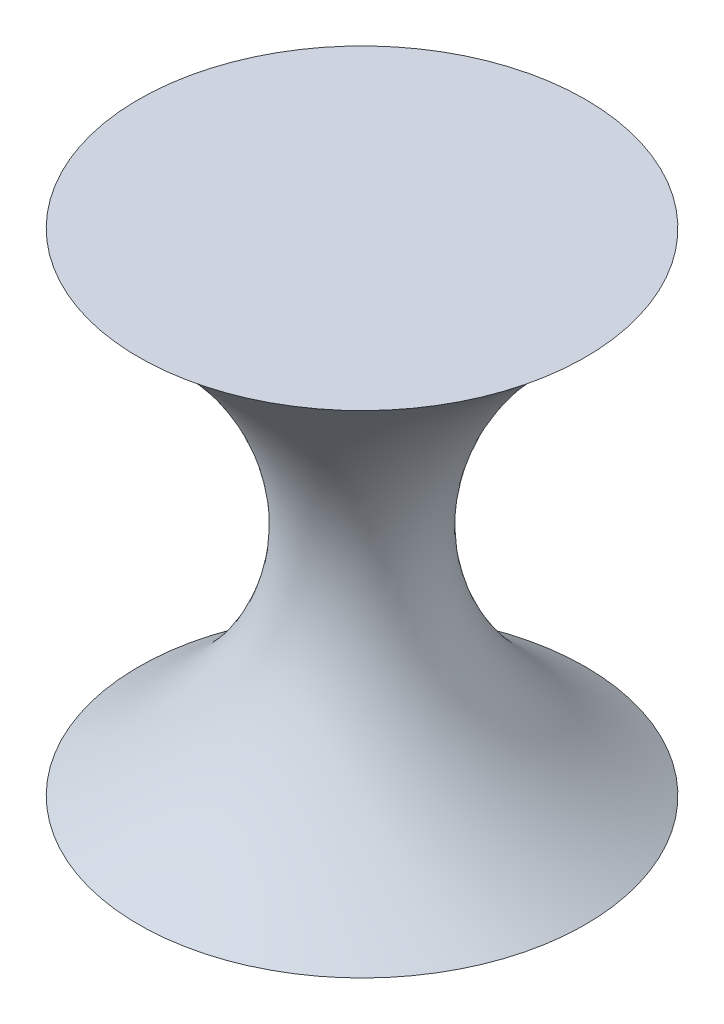
SolidWorks part; units mm, degrees
ref_plane "Front Plane" through (0, 0, 0) normal (0, 0, 1) x (1, 0, 0)
ref_plane "Top Plane" through (0, 0, 0) normal (0, 1, 0) x (1, 0, 0)
ref_plane "Right Plane" through (0, 0, 0) normal (1, 0, 0) x (0, 0, -1)
sketch "Sketch1" plane through (0, 0, 0) normal (0, 0, 1) x (1, 0, 0)
  line L0 (0, 0) -> (0, 100) construction
  line L1 (0, 100) -> (30, 100) construction
  line L2 (30, 100) -> (30, 34) construction
  line L3 (30, 34) -> (0, 34)
  line L4 (0, 34) -> (0, 100)
  line L5 (0, 100) -> (30, 100)
  spline S0 degree 3 poles (30, 100) (1.6934, 77.6934) (1.831, 52.2597) (30, 34) knots 0 0 0 0 1 1 1 1
  dimension "D1" = 30
  dimension "D2" = 66
  dimension "D3" = 100
revolve "Revolve1" add sketch "Sketch1" angle 360 about L0
